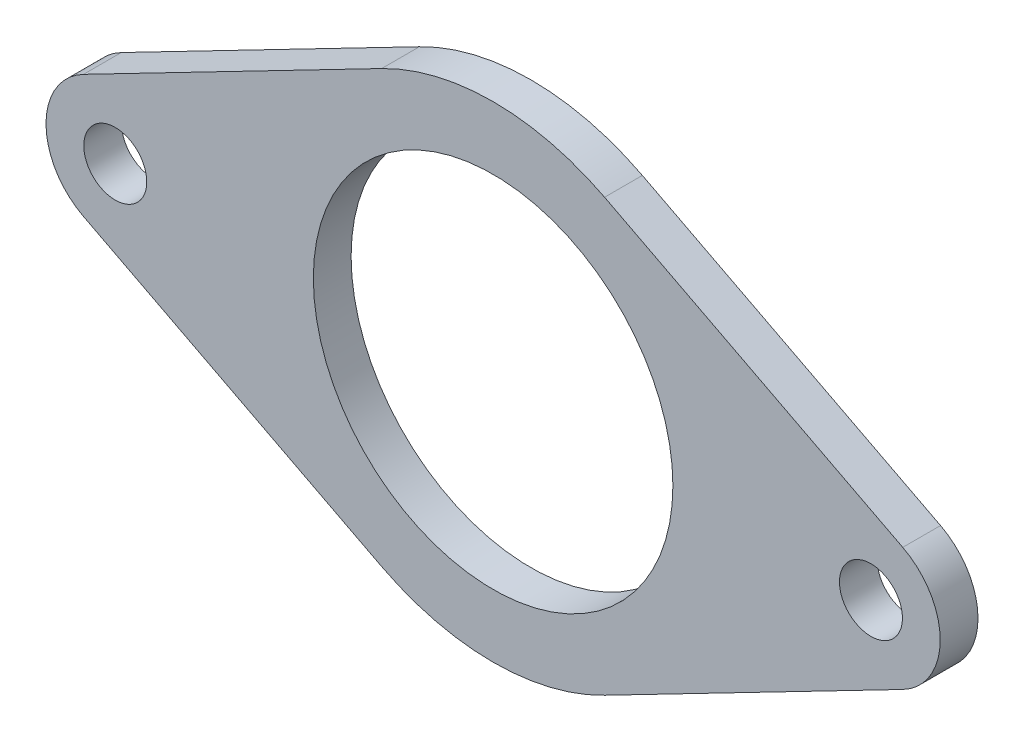
SolidWorks part; units mm, degrees
ref_plane "Front Plane" through (0, 0, 0) normal (0, 0, 1) x (1, 0, 0)
ref_plane "Top Plane" through (0, 0, 0) normal (0, 1, 0) x (1, 0, 0)
ref_plane "Right Plane" through (0, 0, 0) normal (1, 0, 0) x (0, 0, -1)
sketch "Sketch1" plane through (0, 0, 0) normal (0, 0, 1) x (1, 0, 0)
  line L0 (-30, 0) -> (30, 0) construction
  line L5 (-30, 2.5) -> (30, 2.5) construction
  line L6 (-8.8502, 17.1228) -> (-32.5254, 4.8859)
  line L7 (0, 0) -> (0, 19.2748) construction
  line L10 (-8.8502, 17.1228) -> (8.8502, 17.1228) construction
  line L12 (8.8502, 17.1228) -> (32.5254, 4.8859)
  line L19 (8.8502, -17.1228) -> (32.5254, -4.8859)
  line L24 (-8.8502, -17.1228) -> (-32.5254, -4.8859)
  circle A21 centre (0, 0) radius 14.2748
  circle A22 centre (-30, 0) radius 2.5
  circle A23 centre (30, 0) radius 2.5
  arc A24 (-6.5659, -12.6751) -> (6.5659, 12.6751) centre (0, 0) ccw construction
  arc A25 (-6.5659, -12.6751) -> (6.5659, 12.6751) centre (0, 0) ccw
  arc A26 (8.8502, 17.1228) -> (-8.8502, 17.1228) centre (0, 0) ccw
  circle A27 centre (-30, 0) radius 5.5
  arc A28 (6.5659, 12.6751) -> (-6.5659, -12.6751) centre (0, 0) ccw
  arc A29 (-6.5659, -12.6751) -> (6.5659, 12.6751) centre (0, 0) ccw
  arc A30 (6.5659, 12.6751) -> (-6.5659, -12.6751) centre (0, 0) ccw
  arc A31 (-6.5659, -12.6751) -> (6.5659, 12.6751) centre (0, 0) ccw
  circle A32 centre (30, 0) radius 5.5
  arc A33 (8.8502, -17.1228) -> (-8.8502, -17.1228) centre (0, 0) cw
  point P4 (0, 0)
  dimension "D4" = 5
  dimension "D5" = 3
  dimension "D1" = 5
  dimension "D6" = 11
  dimension "D2" = 30
  dimension "D3" = 0
extrude "Boss-Extrude1" add sketch "Sketch1" along normal blind 3
